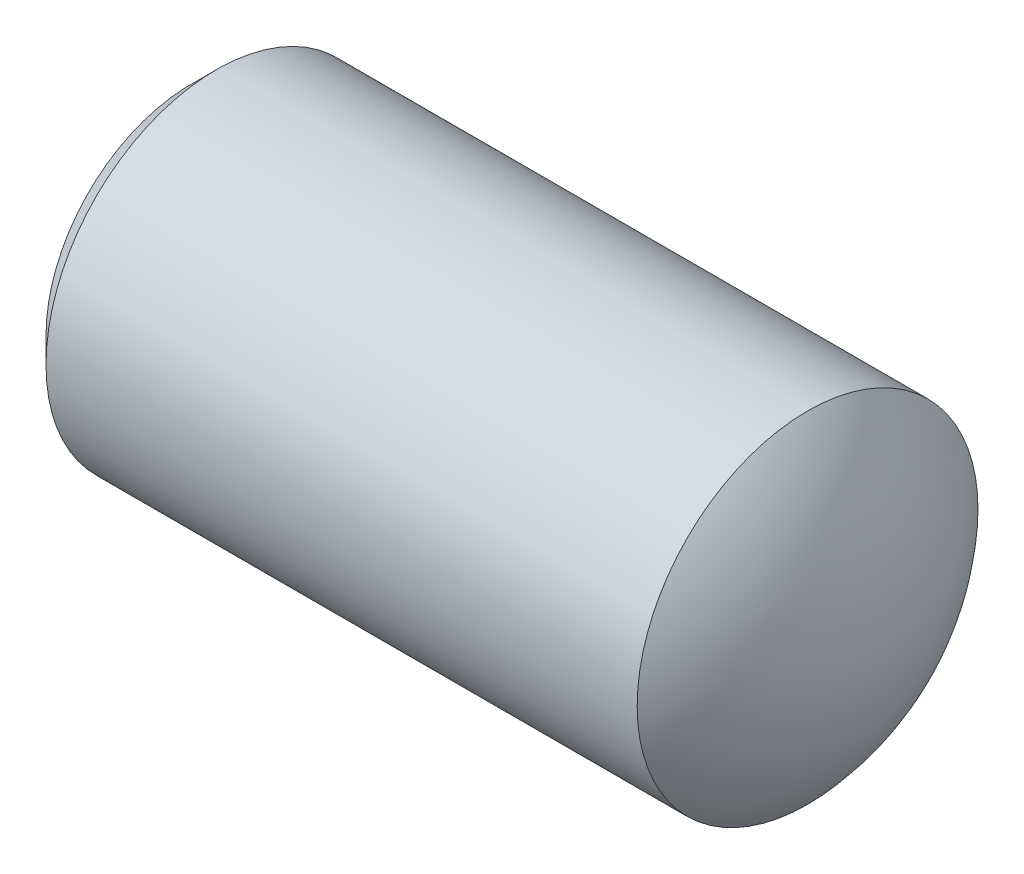
SolidWorks part; units mm, degrees
revolve "BaseBody" add sketch "BodySke" angle 360 about L5
sketch "BodySke" plane through (0, 0, 0) normal (0, 0, 1) x (1, 0, 0)
  line L0 (0, 0) -> (0, 10.8102)
  line L1 (0, 10.8102) -> (1.8898, 12.7)
  line L2 (1.8898, 12.7) -> (45.949, 12.7)
  line L3 (2.1082, 15.875) -> (2.1082, -3.175) construction
  line L4 (50.8, 0) -> (0, 0)
  line L5 (-12.7, 0) -> (88.9, 0) construction
  line L8 (0, -10.8102) -> (1.8898, -12.7) construction
  arc A0 (50.8, 0) -> (45.949, 12.7) centre (31.75, 0) ccw
  dimension "Oval_radius" = 19.05
  dimension "Diameter" = 25.4
  dimension "Drive_ch_ang" = 45
  dimension "Minor_dia" = 21.6205
  dimension "Length" = 50.8
  dimension "Advance" = 2.1082
cosmetic thread "ThreadCosmetic" [suppressed] parameters "Thread_minor"=21.6205
ref_plane "Plane1" through (0, 0, 0) normal (0, 0, 1) x (1, 0, 0)
ref_plane "Plane2" through (0, 0, 0) normal (0, 1, 0) x (1, 0, 0)
ref_plane "Plane3" through (0, 0, 0) normal (1, 0, 0) x (0, 0, -1)
sketch "Sketch2" plane through (0, 0, 0) normal (-1, 0, 0) x (0, 0, 1)
  line L0 (4.1208, 7.1374) -> (-4.1208, 7.1374)
  line L1 (-4.1208, 7.1374) -> (-8.2416, 0)
  line L2 (4.1208, 7.1374) -> (8.2416, 0)
  line L3 (4.1208, -7.1374) -> (8.2416, 0)
  line L4 (4.1208, -7.1374) -> (-4.1208, -7.1374)
  line L5 (-4.1208, -7.1374) -> (-8.2416, 0)
  dimension "Hex_size" = 14.2748
  dimension "D2" = 7.1374
  dimension "D3" = 7.1374
extrude "Hex" cut sketch "Sketch2" against normal blind 14.2748
sketch "Sketch4" plane through (0, 4.7709, -0.5249) normal (-1, 0, 0) x (0, 0, 1)
  line L0 (0.5249, -4.7709) -> (10.6976, -4.7709)
  line L1 (0.5249, -4.7709) -> (6.6732, -1.2211) construction
  line L2 (0.5249, -4.7709) -> (5.6112, 4.0389)
  line L3 (8.9666, -2.6687) -> (10.2861, -1.9069)
  line L4 (6.5663, 1.4888) -> (7.8858, 2.2506)
  arc A0 (8.9666, -2.6687) -> (6.5663, 1.4888) centre (0.5249, -4.7709) ccw
  arc A1 (10.6976, -4.7709) -> (10.2861, -1.9069) centre (0.5249, -4.7709) ccw
  arc A2 (5.6112, 4.0389) -> (7.8858, 2.2506) centre (0.5249, -4.7709) cw
  circle A3 centre (0.5249, -4.7709) radius 8.6995 construction
  circle A4 centre (0.5249, -4.7709) radius 10.1727 construction
  dimension "Spline_n_dim" = 17.399
  dimension "Spline_m_dim" = 20.3454
  dimension "D1" = 30
  dimension "Spline_a_dim" = 60
  dimension "Spline_p_dim" = 4.8006
  dimension "D3" = 2.4003
extrude "Spline" [suppressed] cut sketch "Sketch4" against normal blind 12.7
pattern_circular "CirPattern1" [suppressed] count 6 every 60 about axis through (-12.7, 0, 0) along (1, 0, 0)
sketch "ThdSchSke" plane through (0, 0, 0) normal (0, 0, 1) x (1, 0, 0)
  line L0 (1.8898, -10.8102) -> (0.5665, -12.7)
  line L1 (1.8898, -10.8102) -> (3.213, -12.7)
  line L2 (3.213, -12.7) -> (3.213, -15.875)
  line L3 (-3.175, 0) -> (5.1513, 0) construction
  line L4 (1.8898, 12.7) -> (1.8898, -12.7) construction
  line L5 (3.213, -15.875) -> (0.5665, -15.875)
  line L6 (0.5665, -15.875) -> (0.5665, -12.7)
  dimension "Thread_minor" = 21.6205
  dimension "Diameter" = 25.4
revolve "ThreadSchematic" [suppressed] cut sketch "ThdSchSke" angle 360 about L3
pattern_linear "ThdSchPat" [suppressed]
equation "\"D2@Sketch2\" = \"Hex_size@Sketch2\" / 2"
equation "\"D3@Sketch2\" = \"Hex_size@Sketch2\" / 2"
equation "\"Thread_minor@ThreadCosmetic\" = \"Minor_dia@BodySke\""
equation "\"D1@Sketch4\" = \"Spline_a_dim@Sketch4\" / 2"
equation "\"D3@Sketch4\" = \"Spline_p_dim@Sketch4\" / 2"
equation "\"D2@CirPattern1\" = \"Spline_a_dim@Sketch4\""
equation "\"Num_teeth@CirPattern1\" = 360 / \"D2@CirPattern1\""
equation "\"Thread_minor@ThdSchSke\" = \"Thread_minor@ThreadCosmetic\""
equation "\"Diameter@ThdSchSke\" = \"Diameter@BodySke\""
equation "\"Overcut@ThdSchSke\" = \"Diameter@BodySke\" * 1.25"
equation "\"Num_threads@ThdSchPat\" = int( (\"Length@BodySke\" - ( ( ( \"Diameter@BodySke\" - \"Minor_dia@BodySke\" ) * 0.5 ) / tan( \"Drive_ch_ang@BodySke\" * 0.017453292 ) ) - ( \"Oval_radius@BodySke\" - sqr ( ( \"Oval_radius@BodySke\" * \"Oval_radius@BodySke\" ) - ( ( \"Diameter@BodySke\" * 0.5 ) * ( \"Diameter@BodySke\" * 0.5 ) ) ) ) ) / \"Advance@BodySke\" + 0.999 )  + 1"
equation "\"Advance@ThdSchPat\" = (\"Length@BodySke\" - ( ( ( \"Diameter@BodySke\" - \"Minor_dia@BodySke\" ) * 0.5 ) / tan( \"Drive_ch_ang@BodySke\" * 0.017453292 ) ) - ( \"Oval_radius@BodySke\" - sqr ( ( \"Oval_radius@BodySke\" * \"Oval_radius@BodySke\" ) - ( ( \"Diameter@BodySke\" * 0.5 ) * ( \"Diameter@BodySke\" * 0.5 ) ) ) ) ) /  (\"Num_threads@ThdSchPat\" - 1) 'relax it"
equation "' \"Num_threads@ThdSchPat\" = \"Num_threads@ThdSchPat\" - sgn( \"Num_threads@ThdSchPat\" - 1) '---chamfered tips only---"
